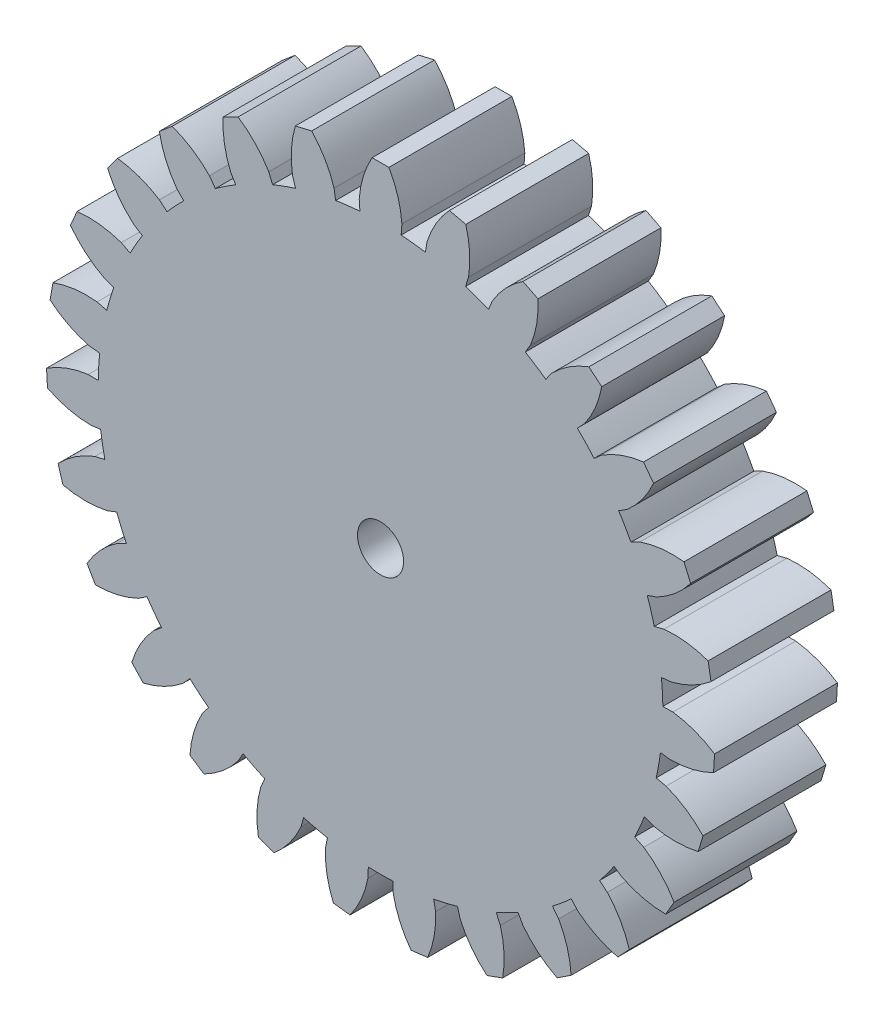
SolidWorks part; units mm, degrees
ref_plane "Front Plane" through (0, 0, 0) normal (0, 0, 1) x (1, 0, 0)
ref_plane "Top Plane" through (0, 0, 0) normal (0, 1, 0) x (1, 0, 0)
ref_plane "Right Plane" through (0, 0, 0) normal (1, 0, 0) x (0, 0, -1)
sketch "Sketch2" plane through (0, 0, 0) normal (0, 0, 1) x (1, 0, 0)
  circle A0 centre (0, 0) radius 18.375
  dimension "D1" = 36.75
extrude "Boss-Extrude1" add sketch "Sketch2" along normal blind 8
sketch "Sketch3" plane through (0, 0, 0) normal (0, 0, 1) x (1, 0, 0)
  line L0 (0, 0) -> (0, 35) construction
  line L1 (0, 0) -> (0.5454, 21.7432) construction
  line L2 (0, 0) -> (1.1773, 20.2157) construction
  line L3 (0, 0) -> (1.3893, 18.9782)
  line L4 (0, 0) -> (-1.3893, 18.9782)
  line L5 (-0.5454, 21.7432) -> (0.5454, 21.7432)
  arc A0 (1.3893, 18.9782) -> (0.5454, 21.7432) centre (-5.0707, 18.5178) ccw
  arc A1 (-1.3893, 18.9782) -> (-0.5454, 21.7432) centre (5.0707, 18.5178) cw
  dimension "D2" = 1.0909
  dimension "D1" = 35
extrude "Boss-Extrude2" add sketch "Sketch3" along normal blind 8
pattern_circular "CirPattern1" count 27 over 360 about axis through (0, 0, 0) along (0, 0, 1) of "Boss-Extrude2"
sketch "Sketch6" plane through (0, 0, 8) normal (0, 0, 1) x (1, 0, 0)
  circle A0 centre (0, 0) radius 1.5
extrude "Cut-Extrude1" cut sketch "Sketch6" against normal blind 8
